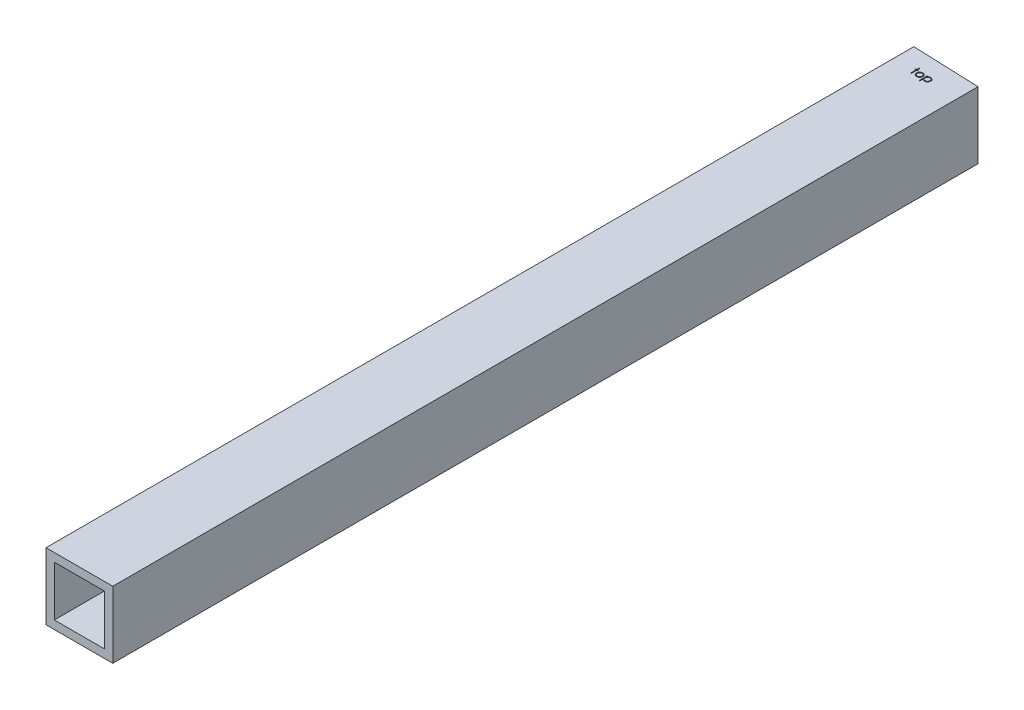
SolidWorks part; units mm, degrees
ref_plane "Front Plane" through (0, 0, 0) normal (0, 0, 1) x (1, 0, 0)
ref_plane "Top Plane" through (0, 0, 0) normal (0, 1, 0) x (1, 0, 0)
ref_plane "Right Plane" through (0, 0, 0) normal (1, 0, 0) x (0, 0, -1)
sketch "Sketch2" plane through (0, 0, 0) normal (0, 0, 1) x (1, 0, 0)
  line L1 (0, 0) -> (25.4, 0)
  line L2 (0, 0) -> (0, 25.4)
  line L3 (0, 25.4) -> (25.4, 25.4)
  line L4 (25.4, 0) -> (25.4, 25.4)
  line L5 (3.175, 22.225) -> (22.225, 22.225)
  line L6 (3.175, 22.225) -> (3.175, 3.175)
  line L7 (3.175, 3.175) -> (22.225, 3.175)
  line L8 (22.225, 22.225) -> (22.225, 3.175)
  dimension "D1" = 25.4
  dimension "D2" = 25.4
  dimension "D3" = 3.175
  dimension "D4" = 3.175
  dimension "D5" = 3.175
  dimension "D6" = 3.175
extrude "Boss-Extrude1" add sketch "Sketch2" along normal blind 330.2
sketch "Sketch3" plane through (0, 25.4, 0) normal (0, 1, 0) x (1, 0, 0)
  line L0 (0, 0) -> (25.4, -0.9775)
  line L1 (25.4, -330.2) -> (25.4, 0) construction
  line L2 (25.4, -0.9775) -> (25.4, 0)
  line L3 (25.4, 0) -> (0, 0)
  text T0 "top"
  dimension "D1" = 87.796
extrude "Cut-Extrude1" cut sketch "Sketch3" against normal through all
